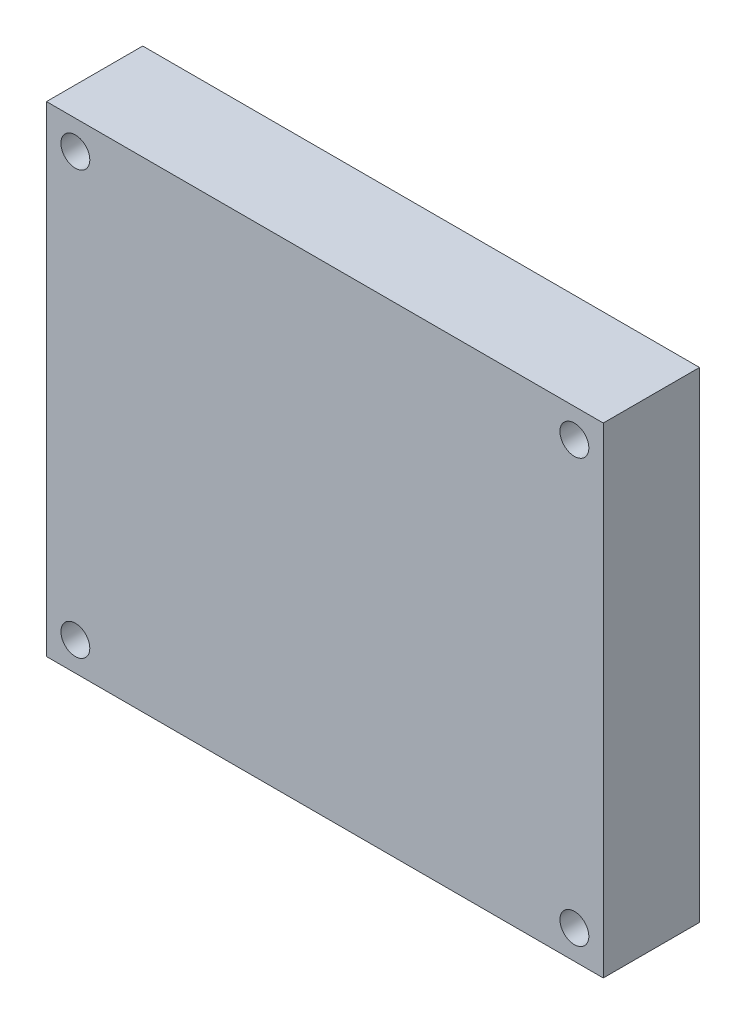
SolidWorks part; units mm, degrees
ref_plane "前视基准面" through (0, 0, 0) normal (0, 0, 1) x (1, 0, 0)
ref_plane "上视基准面" through (0, 0, 0) normal (0, 1, 0) x (1, 0, 0)
ref_plane "右视基准面" through (0, 0, 0) normal (1, 0, 0) x (0, 0, -1)
sketch "草图1" plane through (0, 0, 0) normal (0, 0, 1) x (1, 0, 0)
  line L0 (-3, 3) -> (54.849, 3)
  line L1 (0, 0) -> (51.849, 0) construction
  line L2 (0, 0) -> (0, -43.936) construction
  line L3 (0, -43.936) -> (51.849, -43.936) construction
  line L4 (51.849, 0) -> (51.849, -43.936) construction
  line L9 (54.849, 3) -> (54.849, -46.936)
  line L10 (-3, -46.936) -> (54.849, -46.936)
  line L11 (-3, 3) -> (-3, -46.936)
  circle A0 centre (0, 0) radius 1.5
  circle A1 centre (51.849, 0) radius 1.5
  circle A2 centre (51.849, -43.936) radius 1.5
  circle A3 centre (0, -43.936) radius 1.5
  dimension "D4" = 3
  dimension "D5" = 3
  dimension "D6" = 3
  dimension "D7" = 3
  dimension "D1" = 51.849
  dimension "D2" = 43.936
  dimension "D3" = 3
extrude "凸台-拉伸1" add sketch "草图1" along normal blind 10
